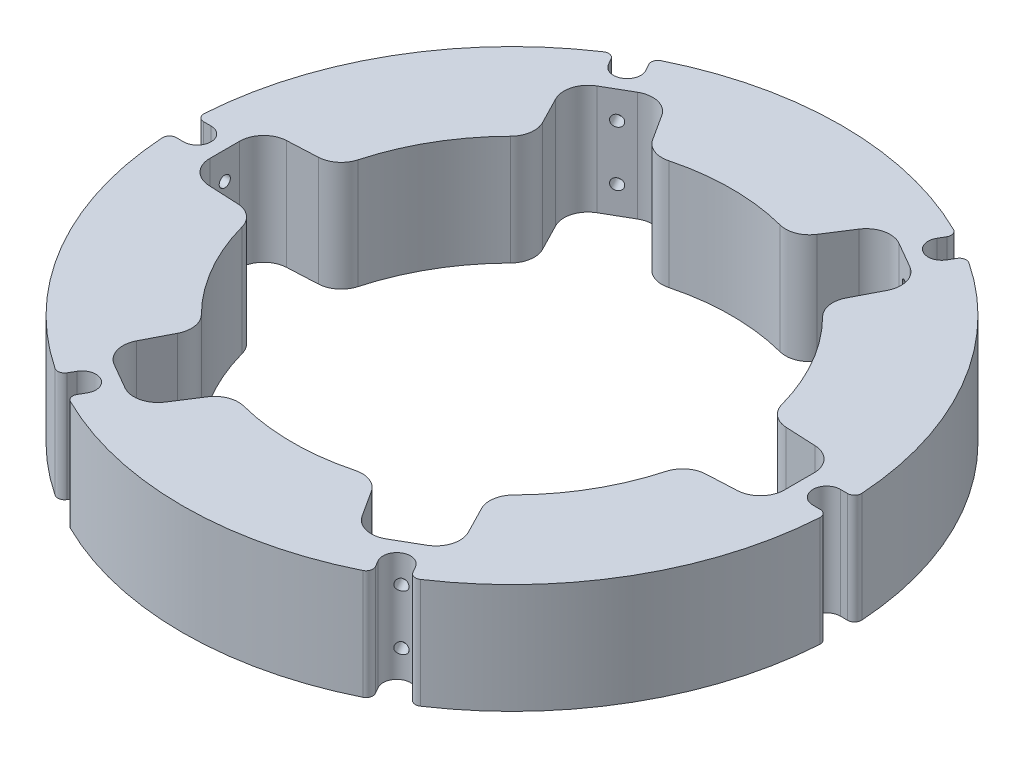
SolidWorks part; units mm, degrees
material "6061-T6 (SS)"
ref_plane "Front Plane" through (0, 0, 0) normal (0, 0, 1) x (1, 0, 0)
ref_plane "Top Plane" through (0, 0, 0) normal (0, 1, 0) x (1, 0, 0)
ref_plane "Right Plane" through (0, 0, 0) normal (1, 0, 0) x (0, 0, -1)
sketch "Sketch1" plane through (0, 0, 0) normal (0, 1, 0) x (1, 0, 0)
  circle A0 centre (0, 0) radius 76.2
  circle A1 centre (0, 0) radius 50.8
  dimension "D1" = 152.4
  dimension "D2" = 101.6
extrude "Boss-Extrude1" add sketch "Sketch1" against normal blind 12.7
sketch "Sketch3" plane through (0, -12.7, 0) normal (0, -1, 0) x (-1, 0, 0)
  line L0 (-76.1338, 3.175) -> (-72.771, 3.175)
  line L1 (-76.1338, -3.175) -> (-72.771, -3.175)
  circle A0 centre (0, 0) radius 76.2 construction
  arc A1 (-72.771, 3.175) -> (-72.771, -3.175) centre (-72.771, 0) cw
  arc A2 (-76.1338, -3.175) -> (-76.1338, 3.175) centre (0, 0) cw
  point P9 (-69.596, 0)
  point P13 (-76.2, 0)
  dimension "D1" = 6.35
  dimension "D2" = 6.604
extrude "Cut-Extrude1" cut sketch "Sketch3" against normal blind 12.7
sketch "Sketch4" plane through (0, -12.7, 0) normal (0, -1, 0) x (-1, 0, 0)
  line L0 (-66.421, 8.7312) -> (-66.421, -8.7312)
  line L1 (-66.421, -8.7312) -> (-49.899, -9.525)
  line L2 (-49.899, -9.525) -> (-49.899, 9.525)
  line L3 (-49.899, 9.525) -> (-66.421, 8.7312)
  line L4 (-66.421, 0) -> (0, 0) construction
  circle A0 centre (0, 0) radius 50.8 construction
  dimension "D1" = 3.175
  dimension "D2" = 19.05
  dimension "D3" = 17.4625
extrude "Cut-Extrude2" cut sketch "Sketch4" against normal through all
hole_wizard "#5-40 Tapped Hole1" positions "Sketch5" profile "Sketch6" tap size "#5-40" standard "ANSI Inch"
sketch "Sketch5" plane through (66.421, 0, 0) normal (-1, 0, 0) x (0, 0, 1)
  line L0 (-8.7312, -12.7) -> (8.7312, -12.7) construction
  point P0 (0, -6.35)
  dimension "D1" = 6.35
sketch "Sketch6" plane through (66.421, -6.35, 0) normal (0, 1, 0) x (0, 0, 1)
  line L0 (0, 0) -> (0, 9.7128)
  line L1 (0, 9.7128) -> (1.289, 9.7128)
  line L2 (1.289, 9.7128) -> (1.289, 0)
  line L5 (1.289, 0) -> (0, 0)
  line L11 (0, -6.35) -> (0, 107.95) construction
  dimension "Thru Tap Drill Dia." = 2.5781
  dimension "Thru Tap Drill Depth" = 9.7128
cosmetic thread "Hole Thread1" parameters "D2"=3.175
fillet "Fillet1" radius 1.5875 2 edges at (76.1338, -6.35, 3.175) (76.1338, -6.35, -3.175)
fillet "Fillet2" radius 5.5562 4 edges at (66.421, -6.35, 8.7312) (66.421, -6.35, -8.7312) (49.899, -6.35, 9.525) (49.899, -6.35, -9.525)
pattern_circular "CirPattern1" count 6 over 360 about axis through (0, 0, 0) along (0, 1, 0) of "Cut-Extrude1", "Cut-Extrude2", "#5-40 Tapped Hole1", "Fillet1", "Fillet2"
cosmetic thread "Hole Thread2" parameters "D2"=3.175
cosmetic thread "Hole Thread3" parameters "D2"=3.175
cosmetic thread "Hole Thread4" parameters "D2"=3.175
cosmetic thread "Hole Thread5" parameters "D2"=3.175
cosmetic thread "Hole Thread6" parameters "D2"=3.175
mirror "Mirror3" about plane through (0, 0, 0) normal (0, 1, 0) of bodies 103
cosmetic thread "Hole Thread8" parameters "D2"=3.175
cosmetic thread "Hole Thread9" parameters "D2"=3.175
cosmetic thread "Hole Thread10" parameters "D2"=3.175
cosmetic thread "Hole Thread11" parameters "D2"=3.175
cosmetic thread "Hole Thread12" parameters "D2"=3.175
cosmetic thread "Hole Thread13" parameters "D2"=3.175
